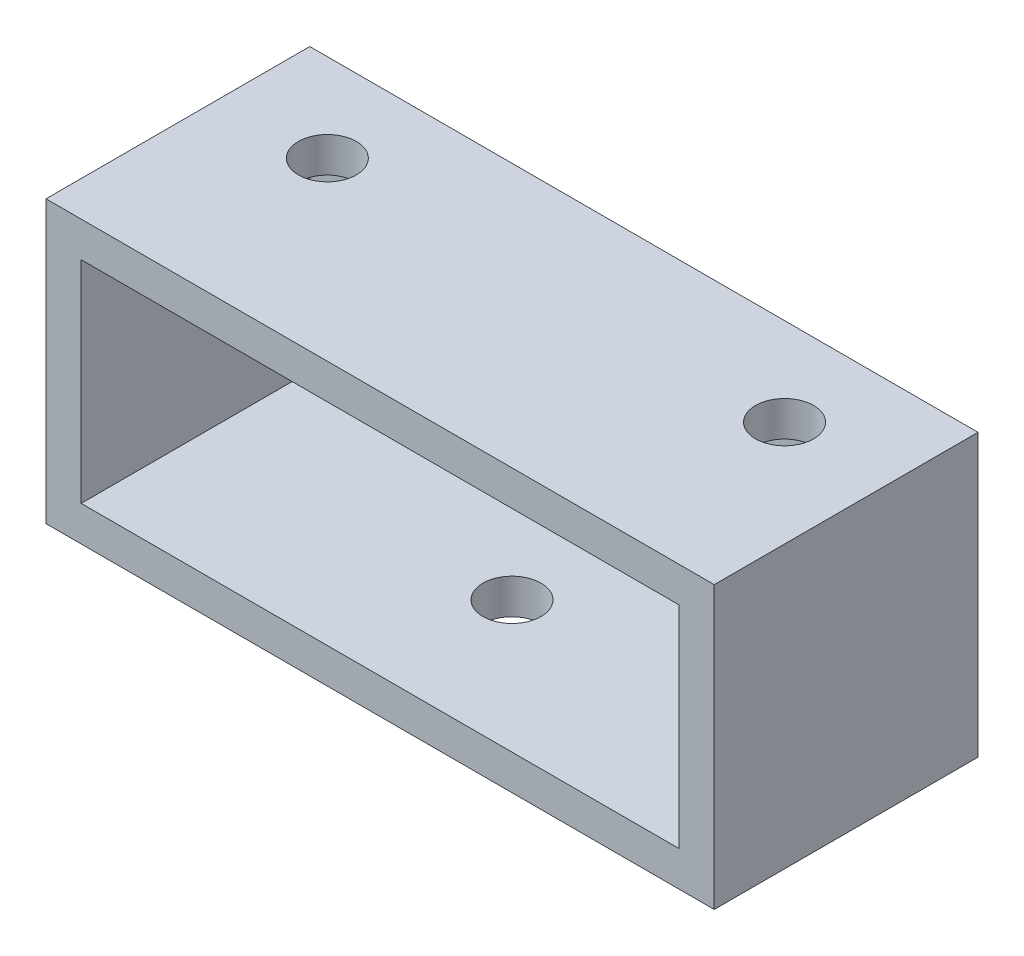
SolidWorks part; units mm, degrees
ref_plane "前视基准面" through (0, 0, 0) normal (0, 0, 1) x (1, 0, 0)
ref_plane "上视基准面" through (0, 0, 0) normal (0, 1, 0) x (1, 0, 0)
ref_plane "右视基准面" through (0, 0, 0) normal (1, 0, 0) x (0, 0, -1)
sketch "草图1" plane through (0, 0, 0) normal (0, 1, 0) x (1, 0, 0)
  line L1 (0, 0) -> (38, 0)
  line L2 (0, 0) -> (0, 15)
  line L3 (0, 15) -> (38, 15)
  line L4 (38, 0) -> (38, 15)
  dimension "D1" = 38
  dimension "D2" = 15
extrude "凸台-拉伸1" add sketch "草图1" along normal blind 16
sketch "草图2" plane through (0, 0, 0) normal (0, 0, 1) x (1, 0, 0)
  line L8 (2, 2) -> (36, 2)
  line L9 (36, 2) -> (36, 14)
  line L10 (36, 14) -> (2, 14)
  line L11 (2, 14) -> (2, 2)
  line L12 (2, 2) -> (36, 2)
  line L13 (36, 2) -> (36, 14)
  line L14 (36, 14) -> (2, 14)
  line L15 (2, 14) -> (2, 2)
  dimension "D1" = 2
extrude "切除-拉伸1" cut sketch "草图2" against normal offset from surface (13 mm away) 2 up to face at (19, 8, -15)
sketch "草图3" plane through (0, 16, 0) normal (0, 1, 0) x (1, 0, 0)
  line L0 (0, 10) -> (38, 10) construction
  line L3 (19, 15) -> (19, -2.8236) construction
  line L4 (38, 15) -> (0, 15) construction
  line L6 (2, 13) -> (36, 13) construction
  circle A0 centre (6, 10) radius 1.65
  circle A1 centre (32, 10) radius 1.65
  dimension "D1" = 3.3
  dimension "D2" = 26
  dimension "D3" = 3
extrude "切除-拉伸2" cut sketch "草图3" against normal blind 2
sketch "草图4" plane through (0, 2, 0) normal (0, 1, 0) x (1, 0, 0)
  line L0 (0, 7.5) -> (39.9529, 7.5) construction
  line L2 (36, 13) -> (36, 0) construction
  line L4 (0, 15) -> (0, 0) construction
  circle A0 centre (19, 7.5) radius 1.65
  circle A1 centre (32, 7.5) radius 1.65
  point P10 (0, 7.5)
  dimension "D1" = 3.3
  dimension "D2" = 3.3
  dimension "D3" = 13
  dimension "D4" = 4
extrude "切除-拉伸3" cut sketch "草图4" against normal blind 10
